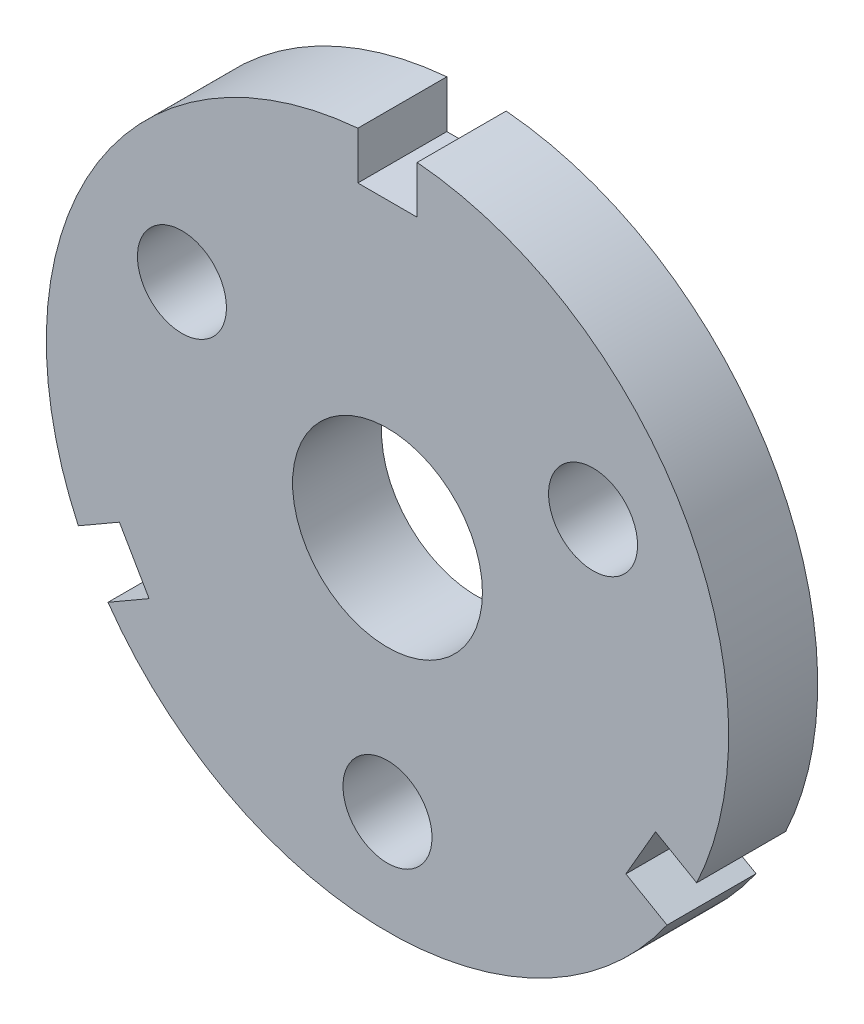
SolidWorks part; units mm, degrees
ref_plane "Front Plane" through (0, 0, 0) normal (0, 0, 1) x (1, 0, 0)
ref_plane "Top Plane" through (0, 0, 0) normal (0, 1, 0) x (1, 0, 0)
ref_plane "Right Plane" through (0, 0, 0) normal (1, 0, 0) x (0, 0, -1)
sketch "Sketch1" plane through (0, 0, 0) normal (0, 0, 1) x (1, 0, 0)
  line L0 (34.641, 20) -> (0, 0) construction
  line L2 (-5, 49.2822) -> (5, 49.2822)
  line L3 (5, 49.2822) -> (5, 57.2822)
  line L4 (-5, 49.2822) -> (-5, 57.2822)
  line L5 (0, -55) -> (0, 55) construction
  line L6 (45.1796, -20.311) -> (52.1078, -24.311)
  line L7 (45.1796, -20.311) -> (40.1796, -28.9712)
  line L8 (40.1796, -28.9712) -> (47.1078, -32.9712)
  line L9 (-40.1796, -28.9712) -> (-47.1078, -32.9712)
  line L10 (-40.1796, -28.9712) -> (-45.1796, -20.311)
  line L11 (-45.1796, -20.311) -> (-52.1078, -24.311)
  circle A0 centre (0, 0) radius 57.5
  circle A1 centre (0, 0) radius 40 construction
  circle A2 centre (0, -40) radius 7.5
  circle A3 centre (-34.641, 20) radius 7.5
  circle A4 centre (34.641, 20) radius 7.5
  circle A5 centre (0, 0) radius 16
  point P13 (0, 0)
  point P14 (0, 49.2822)
  point P19 (0, 0)
  point P20 (0, 0)
  point P30 (0, 0)
  dimension "D1" = 115
  dimension "D2" = 80
  dimension "D3" = 15
  dimension "D5" = 32
  dimension "D6" = 8
  dimension "D7" = 10
  dimension "D4" = 3
  dimension "D8" = 3
extrude "Boss-Extrude1" add sketch "Sketch1" along normal blind 15 contours L4 A0 L11 L10 L9 L8 L7 L6 L3 L2 A5 A4 A3 A2
